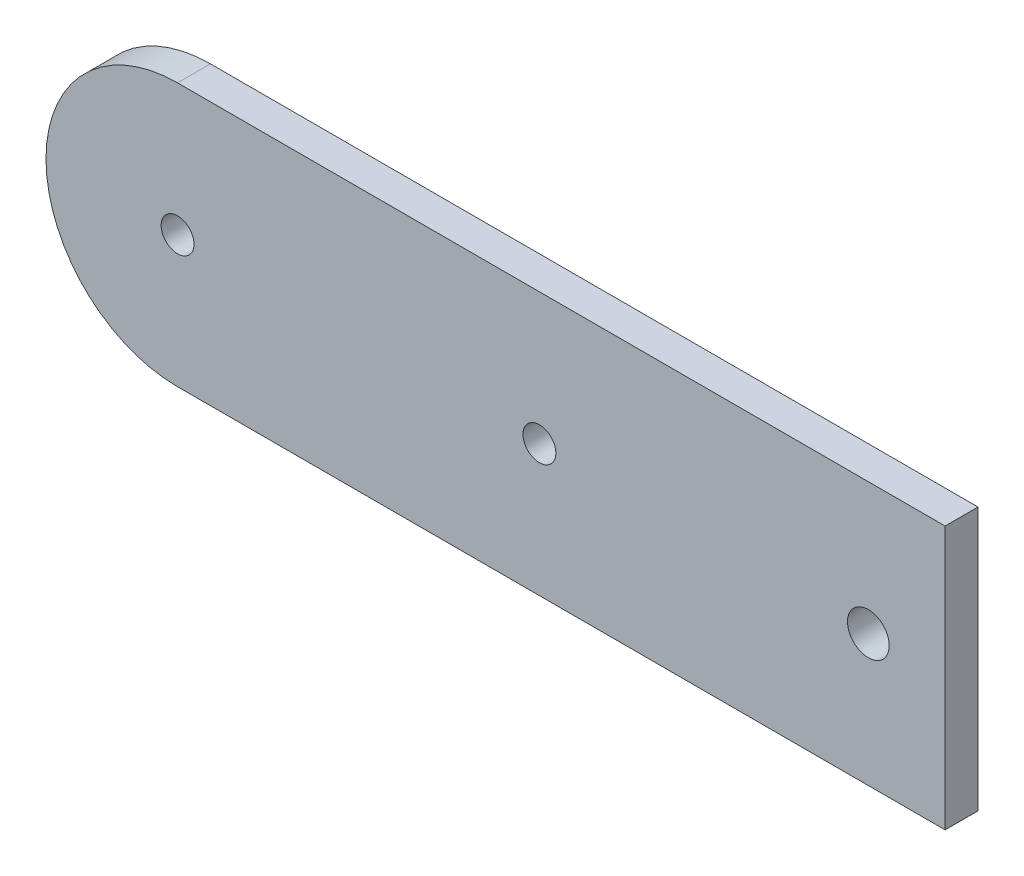
SolidWorks part; units mm, degrees
ref_plane "Plan de face" through (0, 0, 0) normal (0, 0, 1) x (1, 0, 0)
ref_plane "Plan de dessus" through (0, 0, 0) normal (0, 1, 0) x (1, 0, 0)
ref_plane "Plan de droite" through (0, 0, 0) normal (1, 0, 0) x (0, 0, -1)
sketch "Esquisse1" plane through (0, 0, 0) normal (0, 0, 1) x (1, 0, 0)
  line L0 (-107.7461, 0) -> (76.7089, 0) construction
  line L1 (-70, 12) -> (0, 12)
  line L3 (-70, -12) -> (0, -12)
  line L5 (0, 76.9314) -> (0, -56.4335) construction
  line L6 (0, 12) -> (0, -12)
  arc A0 (-70, 12) -> (-70, -12) centre (-70, 0) ccw
  circle A4 centre (-37, 0) radius 1.5
  circle A5 centre (-70, 0) radius 1.5
  circle A6 centre (-7, 0) radius 1.9024
  point P1 (0, 0)
  dimension "D2" = 12
  dimension "D3" = 3
  dimension "D4" = 3
  dimension "D5" = 3.8048
  dimension "D1" = 70
  dimension "D6" = 30
  dimension "D7" = 7
extrude "Boss.-Extru.1" add sketch "Esquisse1" along normal blind 3
